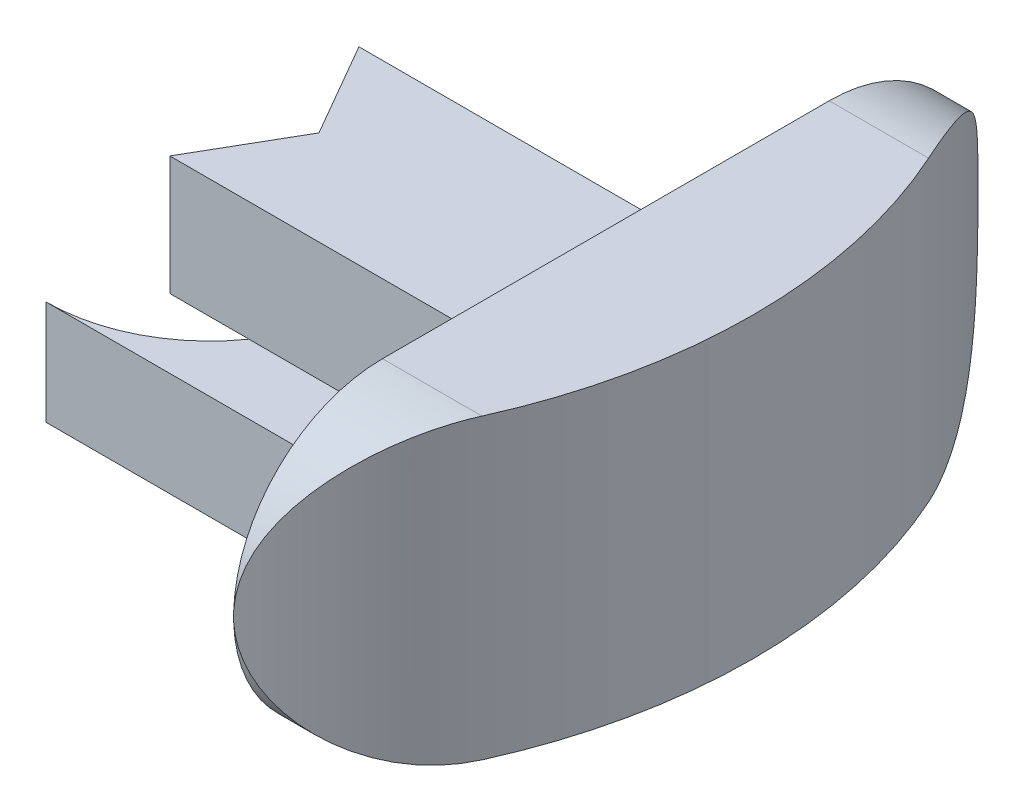
SolidWorks part; units mm, degrees
ref_plane "Front Plane" through (0, 0, 0) normal (0, 0, 1) x (1, 0, 0)
ref_plane "Top Plane" through (0, 0, 0) normal (0, 1, 0) x (1, 0, 0)
ref_plane "Right Plane" through (0, 0, 0) normal (1, 0, 0) x (0, 0, -1)
sketch "Sketch1" plane through (0, 0, 0) normal (0, 1, 0) x (1, 0, 0)
  line L0 (0, 11) -> (34.803, 11)
  line L1 (0, -11) -> (34.803, -11)
  arc A0 (34.803, -11) -> (34.803, 11) centre (0, 0) ccw
  arc A1 (0, -11) -> (0, 11) centre (0, 0) ccw
  dimension "D1" = 73
  dimension "D2" = 22
extrude "Boss-Extrude1" add sketch "Sketch1" along normal blind 7
sketch "Sketch2" plane through (0, 7, 0) normal (0, 1, 0) x (1, 0, 0)
  line L0 (0, 0) -> (46.9867, 0) construction
  line L1 (3.6662, 6.35) -> (35.9434, 6.35)
  line L2 (7.3323, 0) -> (3.6662, 6.35)
  line L7 (3.6662, -6.35) -> (7.3323, 0)
  line L8 (3.6662, -6.35) -> (35.9434, -6.35)
  line L9 (-1.6444, 9.8519) -> (-6.6384, 1.2019) [skipped]
  line L10 (-9.3542, 3.5019) -> (-6.8571, -0.8231) [skipped]
  line L11 (5.8737, -6.35) -> (10.8677, -6.35) [skipped]
  line L12 (7.7098, 6.35) -> (2.7157, 6.35) [skipped]
  arc A0 (5.4993, -3.175) -> (5.4993, 3.175) centre (0, 0) ccw construction
  arc A1 (34.803, -11) -> (34.803, 11) centre (0, 0) ccw construction
  arc A2 (35.9434, 6.35) -> (35.9434, -6.35) centre (0, 0) cw
  dimension "D1" = 12.7
  dimension "D2" = 6.35
  dimension "D3" = 6.35
extrude "Boss-Extrude2" add sketch "Sketch2" along normal blind 8
ref_plane "Plane1" through (26.6, 0, 0) normal (1, 0, 0) x (0, 0, -1)
sketch "Sketch3" plane through (26.6, 0, 0) normal (1, 0, 0) x (0, 0, -1)
  line L0 (-11, 0) -> (11, 0) construction
  line L1 (-15, -1) -> (15, -1)
  line L3 (-15, 19) -> (15, 19)
  arc A0 (15, -1) -> (15, 19) centre (15, 9) ccw
  arc A1 (-15, 19) -> (-15, -1) centre (-15, 9) ccw
  dimension "D1" = 1
  dimension "D2" = 30
  dimension "D3" = 20
extrude "Boss-Extrude3" add sketch "Sketch3" along normal blind 12
sketch "Sketch4" plane through (0, 19, 0) normal (0, 1, 0) x (1, 0, 0)
  circle A2 centre (0, 0) radius 36.5
  circle A4 centre (0, 0) radius 50
  dimension "D1" = 100
  dimension "D2" = 73
extrude "Cut-Extrude1" cut sketch "Sketch4" against normal up to next
